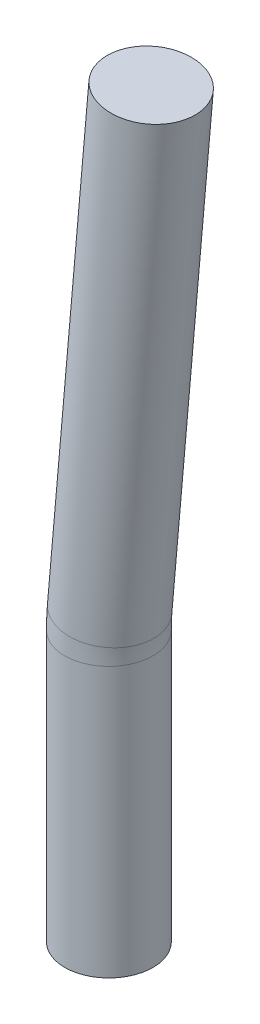
SolidWorks part; units mm, degrees
ref_plane "Front Plane" through (0, 0, 0) normal (0, 0, 1) x (1, 0, 0)
ref_plane "Top Plane" through (0, 0, 0) normal (0, 1, 0) x (1, 0, 0)
ref_plane "Right Plane" through (0, 0, 0) normal (1, 0, 0) x (0, 0, -1)
sketch "Sketch1" plane through (0, 0, 0) normal (0, 0, 1) x (1, 0, 0)
  line L0 (0, 0) -> (0, 18.3451)
  line L1 (0.0571, 19.6524) -> (2.8761, 51.8744)
  arc A0 (0, 18.3451) -> (0.0571, 19.6524) centre (15, 18.3451) cw
  point P6 (0, 19)
  dimension "D3" = 15
  dimension "D1" = 33
  dimension "D2" = 19
  dimension "D4" = 175
sketch "Sketch2" plane through (0, 0, 0) normal (0, 1, 0) x (1, 0, 0)
  circle A0 centre (0, 0) radius 3
  dimension "D1" = 6
sketch "Sketch3" plane through (0, 0, 0) normal (0, 0, 1) x (1, 0, 0)
  circle A0 centre (4, 0) radius 0.5
  dimension "D1" = 1
  dimension "D2" = 4
sweep "Sweep1" add profiles "Sketch2" path "Sketch1"
